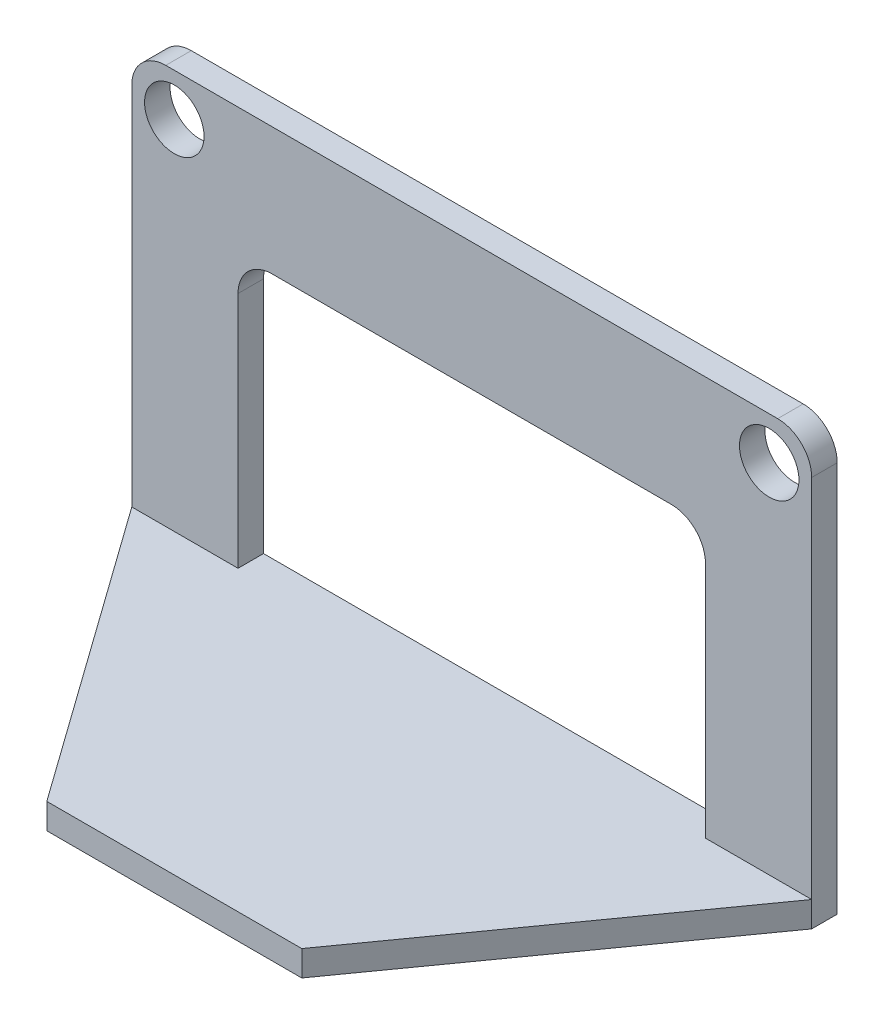
SolidWorks part; units mm, degrees
ref_plane "前视基准面" through (0, 0, 0) normal (0, 0, 1) x (1, 0, 0)
ref_plane "上视基准面" through (0, 0, 0) normal (0, 1, 0) x (1, 0, 0)
ref_plane "右视基准面" through (0, 0, 0) normal (1, 0, 0) x (0, 0, -1)
sketch "草图1" plane through (0, 0, 0) normal (0, 0, 1) x (1, 0, 0)
  line L0 (0, 0) -> (80, 0)
  line L1 (80, 0) -> (80, -50)
  line L2 (80, -50) -> (67.5, -50)
  line L3 (0, -50) -> (0, 0)
  line L4 (12.5, -50) -> (12.5, -15)
  line L5 (12.5, -15) -> (67.5, -15)
  line L6 (67.5, -15) -> (67.5, -50)
  line L8 (12.5, -50) -> (0, -50)
  circle A0 centre (5, -5) radius 3.5
  circle A1 centre (75, -5) radius 3.5
  dimension "D3" = 7
  dimension "D4" = 7
  dimension "D1" = 80
  dimension "D2" = 50
  dimension "D5" = 5
  dimension "D6" = 5
  dimension "D7" = 5
  dimension "D8" = 5
  dimension "D9" = 35
  dimension "D10" = 55
  dimension "D11" = 12.5
extrude "凸台-拉伸1" add sketch "草图1" along normal blind 3
fillet "圆角1" radius 4 1 edges at (0, 0, 1.5)
fillet "圆角2" radius 4 1 edges at (80, 0, 1.5)
fillet "圆角3" radius 4 1 edges at (12.5, -15, 1.5)
fillet "圆角4" radius 4 1 edges at (67.5, -15, 1.5)
sketch "草图2" plane through (0, -50, 0) normal (0, -1, 0) x (1, 0, 0)
  line L0 (0, 3) -> (25, 38)
  line L1 (25, 38) -> (55, 38)
  line L2 (55, 38) -> (80, 3)
  line L3 (80, 3) -> (80, 0)
  line L4 (76, 0) -> (80, 0) construction
  line L5 (80, 3) -> (80, 0) construction
  line L6 (0, 3) -> (0, 0)
  line L7 (0, 0) -> (80, 0)
  dimension "D1" = 30
  dimension "D2" = 25
  dimension "D3" = 35
extrude "凸台-拉伸2" add sketch "草图2" against normal blind 3
